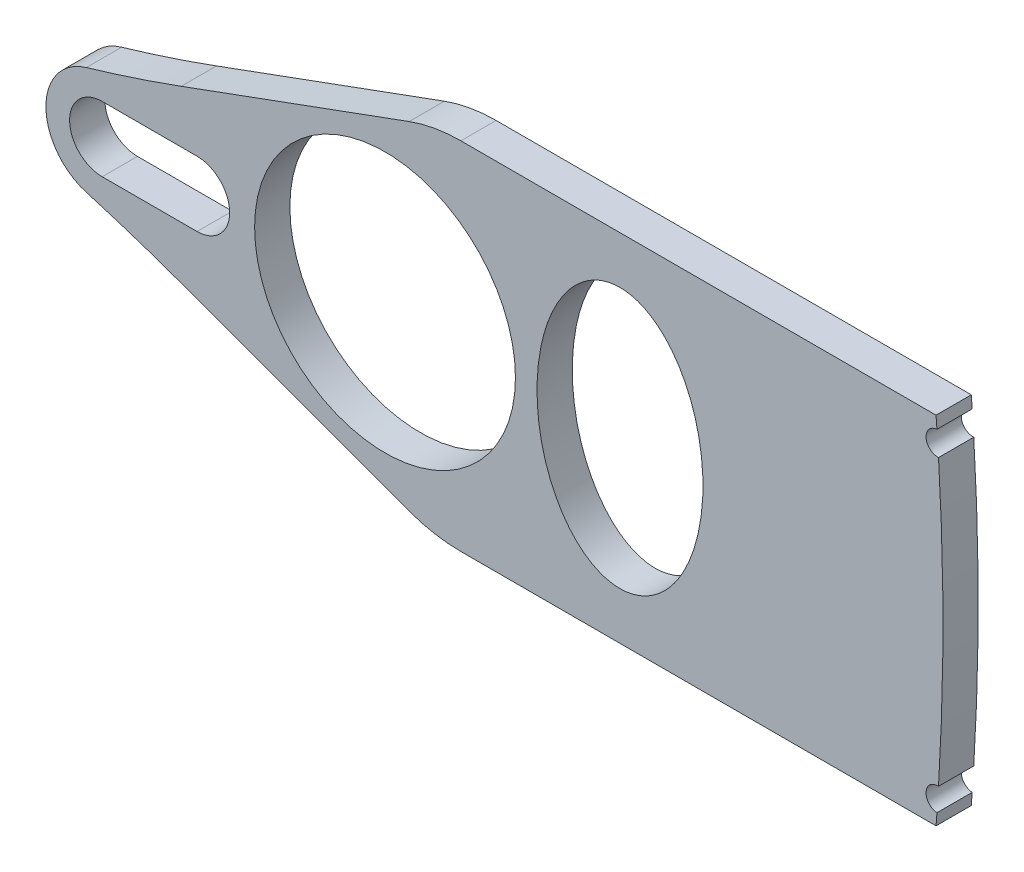
SolidWorks part; units mm, degrees
ref_plane "Front Plane" through (0, 0, 0) normal (0, 0, 1) x (1, 0, 0)
ref_plane "Top Plane" through (0, 0, 0) normal (0, 1, 0) x (1, 0, 0)
ref_plane "Right Plane" through (0, 0, 0) normal (1, 0, 0) x (0, 0, -1)
sketch "Sketch1" plane through (0, 0, 0) normal (0, 0, 1) x (1, 0, 0)
  line L0 (28.8262, 15.1378) -> (5.9104, 15.1378)
  line L1 (1.5045, 14.3568) -> (-17.8942, 7.2554)
  line L2 (-17.8942, -7.2554) -> (1.5045, -14.3568)
  line L3 (5.9104, -15.1378) -> (28.8262, -15.1378)
  line L4 (-16.5455, -2.7753) -> (-24.6191, -2.7753)
  line L5 (-24.6191, 2.7753) -> (-16.5455, 2.7753)
  line L6 (-29.4127, 0) -> (29.4127, 0) construction
  line L7 (19.4545, 15.1378) -> (19.4545, -15.1378) construction
  line L8 (28.8262, 15.1378) -> (46.3587, 15.1378)
  line L9 (28.8262, -15.1378) -> (46.3587, -15.1378)
  arc A6 (5.9104, 15.1378) -> (1.5045, 14.3568) centre (5.9104, 2.3211) ccw
  arc A7 (-25.9651, 4.6008) -> (-17.8942, 7.2554) centre (-61.9532, 127.6116) ccw
  arc A8 (-25.9651, 4.6008) -> (-25.9651, -4.6008) centre (-24.6191, 0) ccw
  arc A9 (-17.8942, -7.2554) -> (-25.9651, -4.6008) centre (-61.9532, -127.6116) ccw
  arc A10 (1.5045, -14.3568) -> (5.9104, -15.1378) centre (5.9104, -2.3211) ccw
  circle A12 centre (-0.5455, 0) radius 11.1011
  arc A13 (-24.6191, 2.7753) -> (-24.6191, -2.7753) centre (-24.6191, 0) ccw
  arc A14 (-16.5455, -2.7753) -> (-16.5455, 2.7753) centre (-16.5455, 0) ccw
  arc A15 (45.5253, -12.9276) -> (46.4342, -14.1315) centre (46.5149, -13.1255) ccw
  arc A16 (46.5696, -12.1178) -> (45.5253, -12.9276) centre (46.5149, -13.1255) ccw
  arc A17 (46.5696, -12.1178) -> (46.5696, 12.1178) centre (-148.7033, 0) ccw
  arc A18 (45.5253, 13.3234) -> (46.5696, 12.1178) centre (46.5149, 13.1255) ccw
  arc A19 (46.4342, 14.1315) -> (45.5253, 13.3234) centre (46.5149, 13.1255) ccw
  arc A20 (46.4342, 14.1315) -> (46.3587, 15.1378) centre (-148.7033, 0) ccw
  arc A21 (46.3587, -15.1378) -> (46.4342, -14.1315) centre (-148.7033, 0) ccw
  ellipse E0 centre (19.4545, 0) end of major axis (19.4545, -11.1011) minor radius 7.0643
  point P42 (-0.5455, 0)
  point P45 (19.4545, 0)
  point P46 (19.4545, 15.1378)
  point P47 (19.4545, -15.1378)
  point P53 (0, 0)
  point P68 (0, 0)
  point P69 (46.3971, 14.6347)
  dimension "D1" = 16
  dimension "D2" = 30.2757
  dimension "D3" = 17.5325
extrude "Boss-Extrude1" add sketch "Sketch1" along normal blind 3
